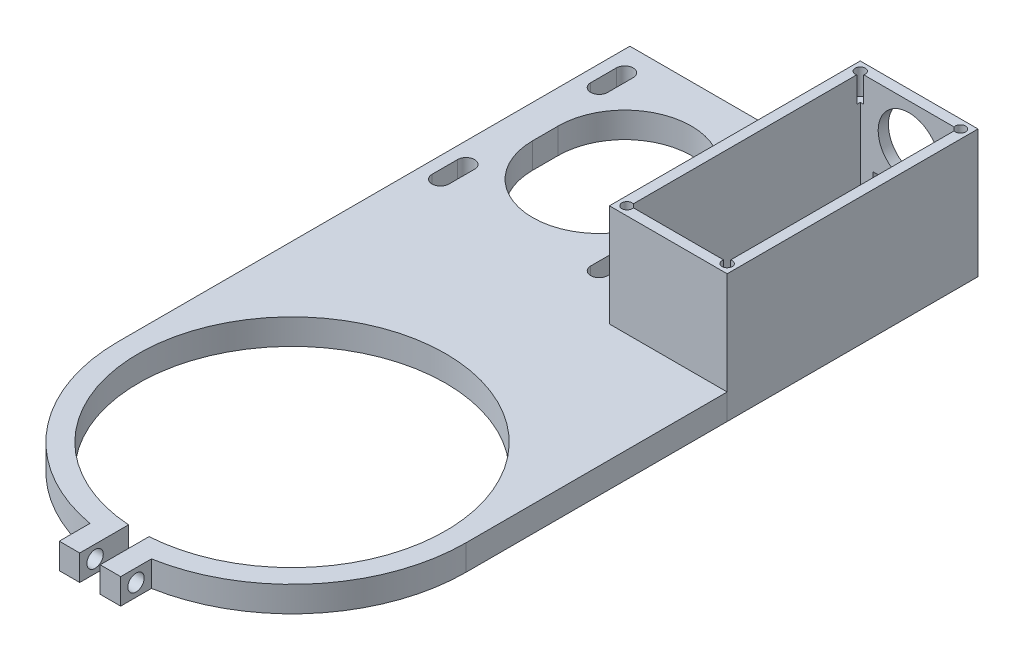
SolidWorks part; units mm, degrees
ref_plane "前视基准面" through (0, 0, 0) normal (0, 0, 1) x (1, 0, 0)
ref_plane "上视基准面" through (0, 0, 0) normal (0, 1, 0) x (1, 0, 0)
ref_plane "右视基准面" through (0, 0, 0) normal (1, 0, 0) x (0, 0, -1)
sketch "草图2" plane through (0, 0, 0) normal (0, 1, 0) x (1, 0, 0)
  line L0 (-2, -29.9333) -> (-2, -39.4664)
  line L4 (2, -29.9333) -> (2, -39.4664)
  line L7 (2, -39.4664) -> (6, -39.4664)
  line L8 (6, -39.4664) -> (6, -33.4664)
  line L9 (-2, -39.4664) -> (-6, -39.4664)
  line L10 (-6, -39.4664) -> (-6, -33.4664)
  line L11 (-34, 0) -> (-34, 100)
  line L12 (-34, 100) -> (11, 100)
  line L13 (34, 51) -> (34, 0)
  line L14 (0, 18.6389) -> (0, -49.9777) construction
  line L15 (-30, 64) -> (-30, 59) construction
  line L16 (-28.35, 64) -> (-28.35, 59)
  line L17 (-31.65, 64) -> (-31.65, 59)
  line L18 (1, 64) -> (1, 59) construction
  line L19 (2.65, 64) -> (2.65, 59)
  line L20 (-0.65, 64) -> (-0.65, 59)
  line L21 (-14.5, 79.5) -> (-14.5, 74.5) construction
  line L22 (-1.5, 79.5) -> (-1.5, 74.5)
  line L23 (-27.5, 79.5) -> (-27.5, 74.5)
  line L24 (-30, 95) -> (-30, 90) construction
  line L25 (-28.35, 95) -> (-28.35, 90)
  line L26 (-31.65, 95) -> (-31.65, 90)
  line L27 (1, 95) -> (1, 90) construction
  line L28 (2.65, 95) -> (2.65, 90)
  line L29 (-0.65, 95) -> (-0.65, 90)
  line L30 (34, 51) -> (11, 51)
  line L31 (11, 51) -> (11, 100)
  arc A3 (-2, -29.9333) -> (2, -29.9333) centre (0, 0) cw
  arc A4 (-34, 0) -> (-6, -33.4664) centre (0, 0) ccw
  arc A5 (6, -33.4664) -> (34, 0) centre (0, 0) ccw
  arc A6 (-28.35, 64) -> (-31.65, 64) centre (-30, 64) ccw
  arc A7 (-31.65, 59) -> (-28.35, 59) centre (-30, 59) ccw
  arc A8 (2.65, 64) -> (-0.65, 64) centre (1, 64) ccw
  arc A9 (-0.65, 59) -> (2.65, 59) centre (1, 59) ccw
  arc A10 (-1.5, 79.5) -> (-27.5, 79.5) centre (-14.5, 79.5) ccw
  arc A11 (-27.5, 74.5) -> (-1.5, 74.5) centre (-14.5, 74.5) ccw
  arc A12 (-28.35, 95) -> (-31.65, 95) centre (-30, 95) ccw
  arc A13 (-31.65, 90) -> (-28.35, 90) centre (-30, 90) ccw
  arc A14 (2.65, 95) -> (-0.65, 95) centre (1, 95) ccw
  arc A15 (-0.65, 90) -> (2.65, 90) centre (1, 90) ccw
  point P8 (-30, 61.5)
  point P23 (1, 61.5)
  point P30 (-14.5, 77)
  point P37 (-30, 92.5)
  point P46 (1, 92.5)
  dimension "D1" = 30
  dimension "D2" = 34
  dimension "D3" = 4
  dimension "D4" = 4
  dimension "D5" = 6
  dimension "D6" = 100
  dimension "D7" = 15.5
  dimension "D8" = 31
  dimension "D9" = 1.65
  dimension "D10" = 31
  dimension "D11" = 5
  dimension "D12" = 4
  dimension "D13" = 5
  dimension "D14" = 5
  dimension "D15" = 13
  dimension "D16" = 49
  dimension "D17" = 23
extrude "凸台-拉伸1" add sketch "草图2" along normal blind 5 contours L8 A5 L13 L30 L31 L12 L11 A4 L10 L9 L0 A3 L4 L7 A15 L29 A14 L28 A13 L26 A12 L25 A11 L23 A10 L22 A9 L20 A8 L19 A7 L17 A6 L16
sketch "草图4" plane through (0, 0, 0) normal (1, 0, 0) x (0, 0, -1)
  line L0 (-36.4664, 5) -> (-36.4664, 0) construction
  line L1 (-33.4664, 2.5) -> (-39.4664, 2.5) construction
  line L4 (-39.4664, 0) -> (-33.4664, 0)
  line L5 (-33.4664, 0) -> (-33.4664, 5)
  line L6 (-33.4664, 5) -> (-39.4664, 5)
  line L7 (-39.4664, 5) -> (-39.4664, 0)
  line L8 (-39.4664, 0) -> (-33.4664, 0) construction
  line L9 (-33.4664, 0) -> (-33.4664, 5) construction
  line L10 (-33.4664, 5) -> (-39.4664, 5) construction
  line L11 (-39.4664, 5) -> (-39.4664, 0) construction
  circle A0 centre (-36.4664, 2.5) radius 1.6
  point P11 (-36.4664, 2.5)
  dimension "D2" = 3.2
  dimension "D1" = 0
extrude "切除-拉伸1" cut sketch "草图4" against normal mid plane 20
sketch "草图5" plane through (0, 0, 0) normal (0, 1, 0) x (1, 0, 0)
  line L0 (11, 100) -> (34, 100)
  line L1 (34, 100) -> (34, 51)
  line L11 (6, -39.4664) -> (6, -33.4664)
  line L12 (34, 0) -> (34, 51)
  line L13 (34, 51) -> (11, 51)
  line L14 (11, 51) -> (11, 100)
  line L15 (11, 100) -> (-34, 100)
  line L16 (-34, 100) -> (-34, 0)
  line L17 (-6, -33.4664) -> (-6, -39.4664)
  line L18 (-6, -39.4664) -> (-2, -39.4664)
  line L19 (-2, -39.4664) -> (-2, -29.9333)
  line L20 (2, -29.9333) -> (2, -39.4664)
  line L21 (2, -39.4664) -> (6, -39.4664)
  line L24 (34, 51) -> (11, 51)
  line L25 (11, 51) -> (11, 100)
  arc A3 (6, -33.4664) -> (34, 0) centre (0, 0) ccw
  arc A4 (-34, 0) -> (-6, -33.4664) centre (0, 0) ccw
  arc A5 (2, -29.9333) -> (-2, -29.9333) centre (0, 0) ccw
  dimension "D1" = 0
extrude "凸台-拉伸2" add sketch "草图5" along normal blind 25 separate body
shell "抽壳1" thickness 2
ref_plane "基准面1" through (0, 0, -100) normal (0, 0, -1) x (-1, 0, 0)
sketch "草图6" plane through (0, 0, -100) normal (0, 0, -1) x (-1, 0, 0)
  line L1 (-29.5, 2.5) -> (-15.5, 2.5)
  line L2 (-29.5, 2.5) -> (-29.5, 9.5)
  line L3 (-29.5, 9.5) -> (-15.5, 9.5)
  line L4 (-34, 0) -> (-11, 0)
  line L5 (-11, 0) -> (-11, 25)
  line L6 (-11, 25) -> (-34, 25)
  line L7 (-34, 25) -> (-34, 0)
  line L8 (-34, 0) -> (-11, 0) construction
  line L9 (-11, 0) -> (-11, 25) construction
  line L10 (-11, 25) -> (-34, 25) construction
  line L11 (-34, 25) -> (-34, 0) construction
  line L12 (-15.5, 2.5) -> (-15.5, 9.5)
  line L13 (-29.5, 2.5) -> (-15.5, 9.5) construction
  line L14 (-29.5, 9.5) -> (-15.5, 2.5) construction
  circle A0 centre (-22.5, 17) radius 6
  point P6 (-22.5, 6)
  point P12 (-22.5, 0)
  dimension "D5" = 12
  dimension "D2" = 14
  dimension "D3" = 7
  dimension "D4" = 2.5
  dimension "D6" = 8
  dimension "D1" = 0
extrude "切除-拉伸2" cut sketch "草图6" against normal up to next (2 mm away)
ref_plane "基准面2" through (0, 25, 0) normal (0, 1, 0) x (1, 0, 0)
sketch "草图7" plane through (0, 25, 0) normal (0, 1, 0) x (1, 0, 0)
  line L0 (11, 100) -> (13, 98) construction
  line L1 (32, 98) -> (34, 100) construction
  line L2 (13, 53) -> (11, 51) construction
  line L3 (32, 53) -> (34, 51) construction
  line L4 (13, 53) -> (32, 53)
  line L5 (13, 98) -> (13, 53)
  line L6 (32, 98) -> (13, 98)
  line L7 (32, 53) -> (32, 98)
  line L8 (13, 53) -> (32, 53) construction
  line L9 (13, 98) -> (13, 53) construction
  line L10 (32, 98) -> (13, 98) construction
  line L11 (32, 53) -> (32, 98) construction
  line L12 (11, 51) -> (34, 51)
  line L13 (34, 51) -> (34, 100)
  line L14 (34, 100) -> (11, 100)
  line L15 (11, 100) -> (11, 51)
  line L16 (11, 51) -> (34, 51) construction
  line L17 (34, 51) -> (34, 100) construction
  line L18 (34, 100) -> (11, 100) construction
  line L19 (11, 100) -> (11, 51) construction
  circle A0 centre (12.7172, 52.7172) radius 1
  circle A1 centre (32.2828, 52.7172) radius 1
  circle A3 centre (32.2828, 98.2828) radius 1
  circle A4 centre (12.7172, 98.2828) radius 1
  dimension "D3" = 2
  dimension "D4" = 0.4
  dimension "D1" = 0
  dimension "D2" = 0
extrude "切除-拉伸3" cut sketch "草图7" against normal blind 5
ref_plane "基准面3" through (0, 2, 0) normal (0, 1, 0) x (1, 0, 0)
sketch "草图10" plane through (0, 2, 0) normal (0, 1, 0) x (1, 0, 0)
  line L0 (22.5, 98) -> (22.5, 53) construction
  line L1 (13, 75.5) -> (32, 75.5) construction
  line L4 (13, 53) -> (32, 53)
  line L5 (32, 53) -> (32, 98)
  line L6 (32, 98) -> (13, 98)
  line L7 (13, 98) -> (13, 53)
  line L8 (13, 53) -> (32, 53) construction
  line L9 (32, 53) -> (32, 98) construction
  line L10 (32, 98) -> (13, 98) construction
  line L11 (13, 98) -> (13, 53) construction
  circle A0 centre (15, 95.75) radius 1
  circle A1 centre (30, 95.75) radius 1
  circle A2 centre (30, 55.25) radius 1
  circle A3 centre (15, 55.25) radius 1
  dimension "D2" = 2
  dimension "D3" = 15
  dimension "D4" = 40.5
  dimension "D1" = 0
extrude "切除-拉伸4" cut sketch "草图10" against normal blind 10
